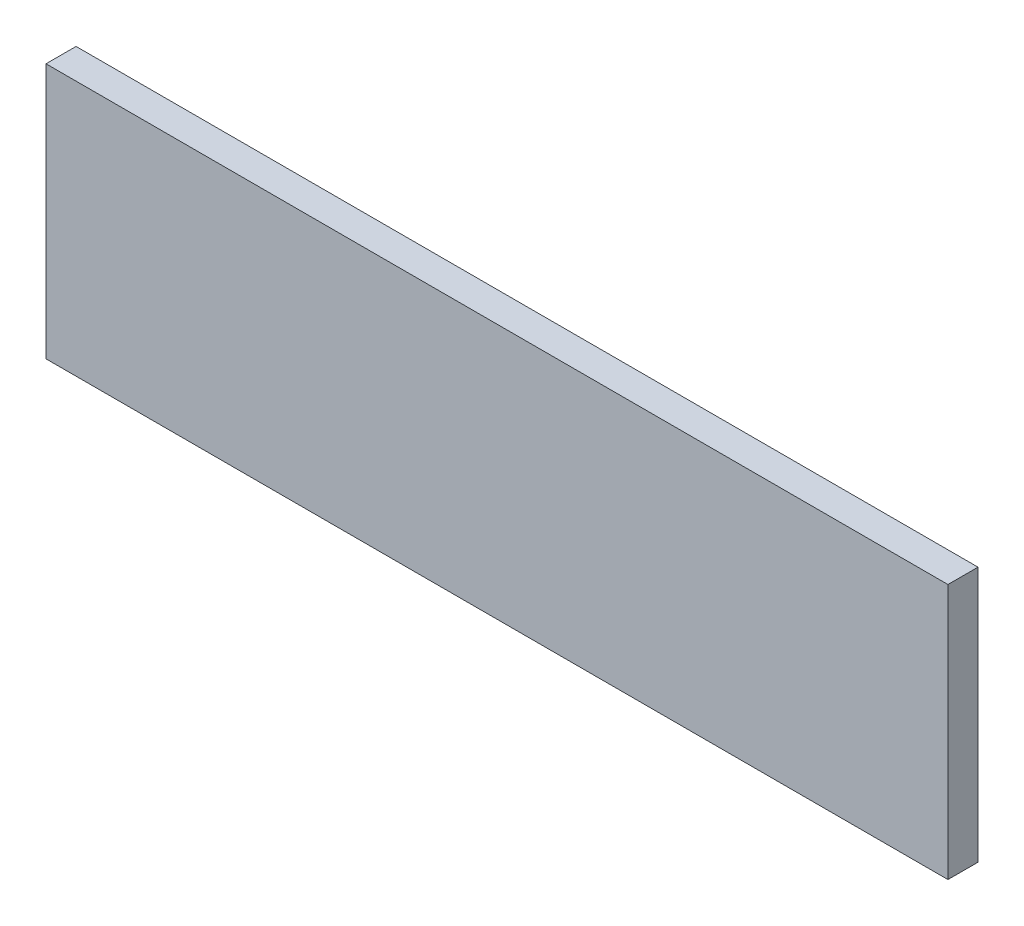
SolidWorks part; units mm, degrees
ref_plane "Plan de face" through (0, 0, 0) normal (0, 0, 1) x (1, 0, 0)
ref_plane "Plan de dessus" through (0, 0, 0) normal (0, 1, 0) x (1, 0, 0)
ref_plane "Plan de droite" through (0, 0, 0) normal (1, 0, 0) x (0, 0, -1)
sketch "Esquisse1" plane through (0, 0, 0) normal (0, 0, 1) x (1, 0, 0)
  line L1 (-36.1663, 22.3328) -> (113.8337, 22.3328)
  line L2 (-36.1663, 22.3328) -> (-36.1663, -20.1672)
  line L3 (-36.1663, -20.1672) -> (113.8337, -20.1672)
  line L4 (113.8337, 22.3328) -> (113.8337, -20.1672)
  dimension "D1" = 42.5
  dimension "D2" = 150
extrude "Boss.-Extru.1" add sketch "Esquisse1" along normal blind 5
